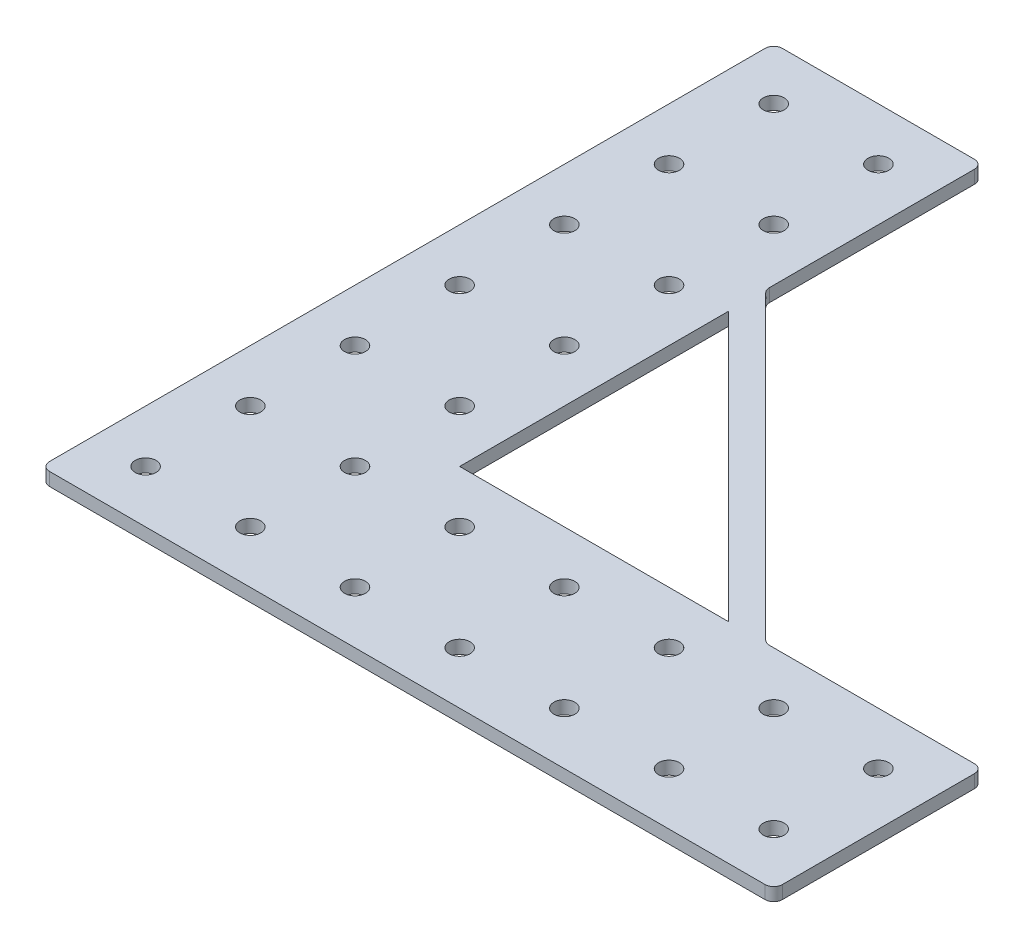
SolidWorks part; units mm, degrees
material "6061 Alloy"
ref_plane "Front Plane" through (0, 0, 0) normal (0, 0, 1) x (1, 0, 0)
ref_plane "Top Plane" through (0, 0, 0) normal (0, 1, 0) x (1, 0, 0)
ref_plane "Right Plane" through (0, 0, 0) normal (1, 0, 0) x (0, 0, -1)
sketch "Sketch1" plane through (0, 0, 0) normal (0, 1, 0) x (1, 0, 0)
  line L0 (-92.7288, 61.0501) -> (-92.7288, -112.5615)
  line L1 (-90.6346, -114.6557) -> (82.977, -114.6557)
  line L2 (85.0712, -112.5615) -> (85.0712, -65.9499)
  line L5 (-44.023, 63.1443) -> (-90.6346, 63.1443)
  line L8 (31.7212, -63.2423) -> (-41.3154, 9.7944)
  line L10 (33.2021, -63.8557) -> (82.977, -63.8557)
  line L11 (-41.9288, 61.0501) -> (-41.9288, 11.2752)
  line L22 (-41.9288, 1.4275) -> (-41.9288, -63.8557)
  line L23 (-41.9288, -63.8557) -> (23.3543, -63.8557)
  line L24 (23.3543, -63.8557) -> (-41.9288, 1.4275)
  circle A0 centre (-80.0288, 50.4443) radius 2.54
  circle A1 centre (-54.6288, 50.4443) radius 2.54
  circle A2 centre (-54.6288, 25.0443) radius 2.54
  circle A3 centre (-54.6288, -0.3557) radius 2.54
  circle A4 centre (-54.6288, -25.7557) radius 2.54
  circle A5 centre (-54.6288, -51.1557) radius 2.54
  circle A7 centre (-80.0288, 25.0443) radius 2.54
  circle A8 centre (-80.0288, -0.3557) radius 2.54
  circle A9 centre (-80.0288, -25.7557) radius 2.54
  circle A10 centre (-80.0288, -51.1557) radius 2.54
  circle A11 centre (-80.0288, -76.5557) radius 2.54
  circle A19 centre (-54.6288, -76.5557) radius 2.54
  circle A20 centre (-80.0288, -101.9557) radius 2.54
  circle A21 centre (-54.6288, -101.9557) radius 2.54
  circle A22 centre (-29.2288, -101.9557) radius 2.54
  circle A23 centre (-3.8288, -101.9557) radius 2.54
  circle A24 centre (21.5712, -101.9557) radius 2.54
  circle A25 centre (46.9712, -101.9557) radius 2.54
  circle A26 centre (72.3712, -101.9557) radius 2.54
  circle A27 centre (-3.8288, -76.5557) radius 2.54
  circle A28 centre (21.5712, -76.5557) radius 2.54
  circle A29 centre (46.9712, -76.5557) radius 2.54
  circle A30 centre (72.3712, -76.5557) radius 2.54
  circle A31 centre (-29.2288, -76.5557) radius 2.54
  circle A32 centre (-54.6288, -76.5557) radius 2.54 [skipped]
  arc A33 (-92.7288, -112.5615) -> (-90.6346, -114.6557) centre (-90.6346, -112.5615) ccw
  arc A34 (82.977, -114.6557) -> (85.0712, -112.5615) centre (82.977, -112.5615) ccw
  arc A35 (85.0712, -65.9499) -> (82.977, -63.8557) centre (82.977, -65.9499) ccw
  arc A36 (33.2021, -63.8557) -> (31.7212, -63.2423) centre (33.2021, -61.7615) cw
  arc A37 (-41.3154, 9.7944) -> (-41.9288, 11.2752) centre (-39.8346, 11.2752) cw
  arc A38 (-41.9288, 61.0501) -> (-44.023, 63.1443) centre (-44.023, 61.0501) ccw
  arc A39 (-92.7288, 61.0501) -> (-90.6346, 63.1443) centre (-90.6346, 61.0501) cw
  point P39 (-92.7288, -114.6557)
  point P65 (85.0712, -114.6557)
  point P68 (85.0712, -63.8557)
  point P71 (32.3346, -63.8557)
  point P74 (-41.9288, 10.4077)
  point P77 (-41.9288, 63.1443)
  point P80 (-92.7288, 63.1443)
  dimension "D5" = 5.08
  dimension "D6" = 12.7
  dimension "D9" = 12.7
  dimension "D10" = 5.08
  dimension "D11" = 25.4
  dimension "D17" = 65.2832
  dimension "D15" = 5
  dimension "D16" = 2
  dimension "D18" = 2.0942
  dimension "D1" = 177.8
  dimension "D2" = 177.8
  dimension "D3" = 50.8
  dimension "D4" = 50.8
  dimension "D14" = 45
  dimension "D12" = 45
  dimension "D13" = 6.35
  dimension "D19" = 103.2894
  dimension "D7" = 2
  dimension "D8" = 7
extrude "Boss-Extrude1" add sketch "Sketch1" along normal blind 3.175
